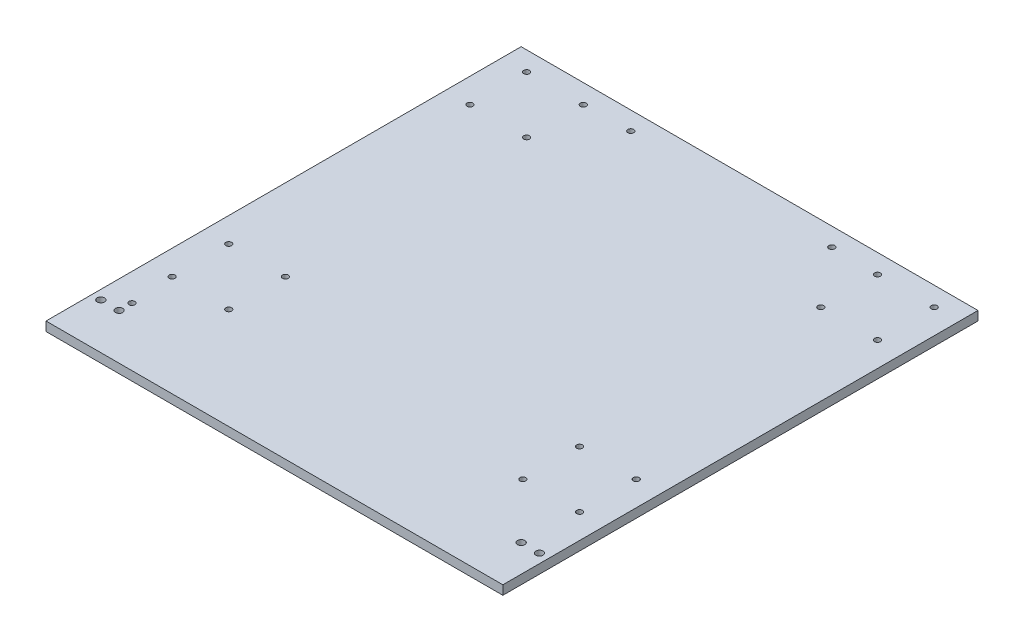
SolidWorks part; units mm, degrees
ref_plane "前视基准面" through (0, 0, 0) normal (0, 0, 1) x (1, 0, 0)
ref_plane "上视基准面" through (0, 0, 0) normal (0, 1, 0) x (1, 0, 0)
ref_plane "右视基准面" through (0, 0, 0) normal (1, 0, 0) x (0, 0, -1)
sketch "草图1" plane through (0, 0, 0) normal (0, 1, 0) x (1, 0, 0)
  line L0 (-125, 83) -> (-75, 83) construction
  line L1 (-125, -130) -> (125, -130)
  line L2 (-125, -130) -> (-125, 130)
  line L3 (-125, 130) -> (125, 130)
  line L4 (125, -130) -> (125, 130)
  line L5 (-125, -130) -> (125, 130) construction
  line L6 (-125, 130) -> (125, -130) construction
  line L7 (-125, -80) -> (-75, -80) construction
  line L8 (-125, -80) -> (-125, -38) construction
  line L9 (-125, -38) -> (-75, -38) construction
  line L10 (-75, -80) -> (-75, -38) construction
  line L11 (-117, -80) -> (-75, -80) construction
  line L12 (-117, -80) -> (-117, -38) construction
  line L13 (-117, -38) -> (-75, -38) construction
  line L14 (-75, -80) -> (-75, -38) construction
  line L15 (-117, -80) -> (-75, -38) construction
  line L16 (-117, -38) -> (-75, -80) construction
  line L17 (-111.5, -43.5) -> (-80.5, -43.5) construction
  line L18 (-111.5, -43.5) -> (-111.5, -74.5) construction
  line L19 (-111.5, -74.5) -> (-80.5, -74.5) construction
  line L20 (-80.5, -43.5) -> (-80.5, -74.5) construction
  line L21 (-125, 83) -> (-125, 125) construction
  line L22 (-125, 125) -> (-75, 125) construction
  line L23 (-75, 83) -> (-75, 125) construction
  line L24 (-117, 83) -> (-75, 83) construction
  line L25 (-117, 83) -> (-117, 125) construction
  line L26 (-117, 125) -> (-75, 125) construction
  line L27 (-75, 83) -> (-75, 125) construction
  line L28 (-117, 83) -> (-75, 125) construction
  line L29 (-117, 125) -> (-75, 83) construction
  line L30 (-111.5, 119.5) -> (-80.5, 119.5) construction
  line L31 (-111.5, 119.5) -> (-111.5, 88.5) construction
  line L32 (-111.5, 88.5) -> (-80.5, 88.5) construction
  line L33 (-80.5, 119.5) -> (-80.5, 88.5) construction
  line L34 (0, -130) -> (0, 130) construction
  line L35 (80.5, -43.5) -> (80.5, -74.5) construction
  line L36 (111.5, -74.5) -> (80.5, -74.5) construction
  line L37 (111.5, -43.5) -> (111.5, -74.5) construction
  line L38 (111.5, -43.5) -> (80.5, -43.5) construction
  line L39 (117, -38) -> (75, -80) construction
  line L40 (117, -80) -> (75, -38) construction
  line L41 (75, -80) -> (75, -38) construction
  line L42 (117, -38) -> (75, -38) construction
  line L43 (117, -80) -> (117, -38) construction
  line L44 (117, -80) -> (75, -80) construction
  line L45 (75, -80) -> (75, -38) construction
  line L46 (125, -38) -> (75, -38) construction
  line L47 (125, -80) -> (125, -38) construction
  line L48 (125, -80) -> (75, -80) construction
  line L49 (80.5, 119.5) -> (80.5, 88.5) construction
  line L50 (111.5, 88.5) -> (80.5, 88.5) construction
  line L51 (111.5, 119.5) -> (111.5, 88.5) construction
  line L52 (111.5, 119.5) -> (80.5, 119.5) construction
  line L53 (117, 125) -> (75, 83) construction
  line L54 (117, 83) -> (75, 125) construction
  line L55 (75, 83) -> (75, 125) construction
  line L56 (117, 125) -> (75, 125) construction
  line L57 (117, 83) -> (117, 125) construction
  line L58 (117, 83) -> (75, 83) construction
  line L59 (75, 83) -> (75, 125) construction
  line L60 (125, 125) -> (75, 125) construction
  line L61 (125, 83) -> (125, 125) construction
  line L62 (125, 83) -> (75, 83) construction
  circle A0 centre (-111.5, 119.5) radius 1.6
  circle A1 centre (-80.5, 119.5) radius 1.6
  circle A2 centre (-80.5, 88.5) radius 1.6
  circle A3 centre (-111.5, 88.5) radius 1.6
  circle A4 centre (-111.5, -43.5) radius 1.6
  circle A5 centre (-80.5, -43.5) radius 1.6
  circle A6 centre (-80.5, -74.5) radius 1.6
  circle A7 centre (-111.5, -74.5) radius 1.6
  circle A8 centre (111.5, -74.5) radius 1.6
  circle A9 centre (80.5, -74.5) radius 1.6
  circle A10 centre (80.5, -43.5) radius 1.6
  circle A11 centre (111.5, -43.5) radius 1.6
  circle A12 centre (111.5, 88.5) radius 1.6
  circle A13 centre (80.5, 88.5) radius 1.6
  circle A14 centre (80.5, 119.5) radius 1.6
  circle A15 centre (111.5, 119.5) radius 1.6
  circle A16 centre (-120, -105) radius 2
  circle A17 centre (-110, -105) radius 2
  circle A18 centre (110, -105) radius 2
  circle A19 centre (120, -105) radius 2
  circle A20 centre (-55, 120) radius 1.6
  circle A21 centre (55, 120) radius 1.6
  circle A23 centre (-110, -98) radius 1.6
  point P0 (0, 0)
  point P10 (-96, -59)
  point P22 (-96, 104)
  point P38 (-96, 104)
  point P45 (-96, -59)
  point P58 (96, -59)
  point P73 (96, 104)
  point P89 (0, 0)
  point P90 (0, 0)
  dimension "D14" = 3.2
  dimension "D15" = 3.2
  dimension "D9" = 10
  dimension "D17" = 4
  dimension "D18" = 4
  dimension "D22" = 10
  dimension "D23" = 3.2
  dimension "D21" = 55
  dimension "D24" = 3.2
  dimension "D25" = 15
  dimension "D26" = 18
  dimension "D1" = 250
  dimension "D2" = 260
  dimension "D3" = 50
  dimension "D4" = 5
  dimension "D5" = 42
  dimension "D6" = 31
  dimension "D7" = 50
  dimension "D8" = 42
  dimension "D10" = 31
  dimension "D11" = 50
  dimension "D12" = 5
  dimension "D19" = 25
  dimension "D20" = 25
  dimension "D13" = 4
  dimension "D16" = 4
extrude "凸台-拉伸1" add sketch "草图1" along normal blind 5
